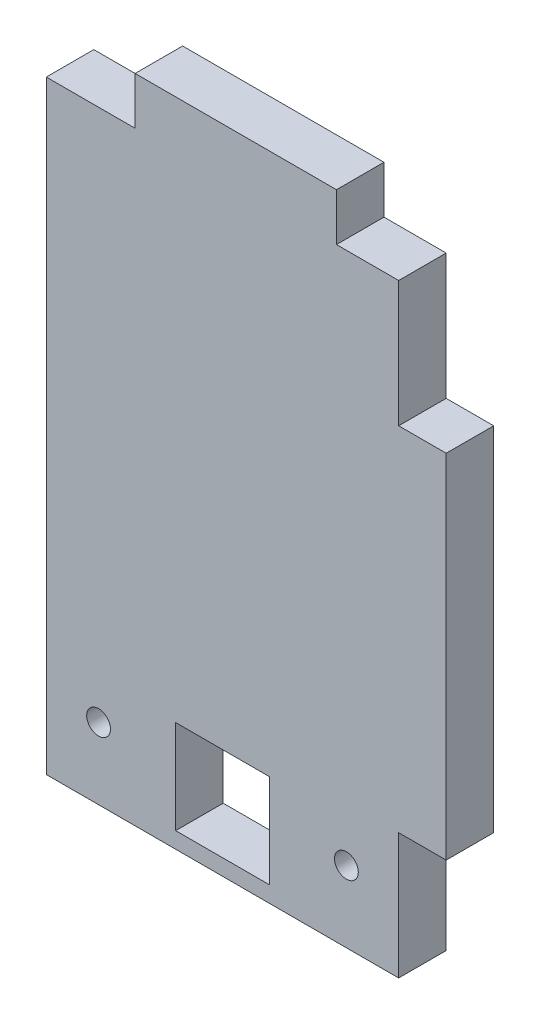
SolidWorks part; units mm, degrees
ref_plane "Front Plane" through (0, 0, 0) normal (0, 0, 1) x (1, 0, 0)
ref_plane "Top Plane" through (0, 0, 0) normal (0, 1, 0) x (1, 0, 0)
ref_plane "Right Plane" through (0, 0, 0) normal (1, 0, 0) x (0, 0, -1)
sketch "Sketch1" plane through (0, 0, 0) normal (0, 0, 1) x (1, 0, 0)
  line L0 (44.45, -60.325) -> (50.4444, -60.325)
  line L1 (0, 0) -> (11.2035, 0)
  line L2 (0, 0) -> (0, -76.2)
  line L3 (0, -76.2) -> (44.45, -76.2)
  line L4 (44.45, 0) -> (44.45, -15.875)
  line L5 (50.4444, -60.325) -> (50.4444, -15.875)
  line L6 (50.4444, -15.875) -> (44.45, -15.875)
  line L7 (44.45, -60.325) -> (44.45, -76.2)
  line L8 (11.2035, 0) -> (11.2035, 5.9944)
  line L9 (11.2035, 5.9944) -> (36.6035, 5.9944)
  line L10 (36.6035, 5.9944) -> (36.6035, 0)
  line L11 (36.6035, 0) -> (44.45, 0)
  line L13 (16.3195, -62.357) -> (28.1305, -62.357)
  line L14 (16.3195, -62.357) -> (16.3195, -74.168)
  line L15 (16.3195, -74.168) -> (28.1305, -74.168)
  line L16 (28.1305, -62.357) -> (28.1305, -74.168)
  circle A2 centre (6.595, -67.2) radius 1.5
  circle A3 centre (37.855, -67.2) radius 1.5
  point P7 (50.4444, -38.1)
  point P12 (0, -38.1)
  point P23 (22.225, -74.168)
  point P24 (22.225, -76.2)
  dimension "D3" = 6.595
  dimension "D4" = 6.595
  dimension "D9" = 3
  dimension "D10" = 3
  dimension "D1" = 44.45
  dimension "D2" = 76.2
  dimension "D5" = 44.45
  dimension "D6" = 5.9944
  dimension "D7" = 5.9944
  dimension "D8" = 25.4
  dimension "D11" = 9
  dimension "D12" = 9
  dimension "D13" = 13.8409
  dimension "D14" = 11.811
  dimension "D15" = 11.811
  dimension "D16" = 2.032
extrude "Boss-Extrude1" add sketch "Sketch1" along normal blind 5.9944
